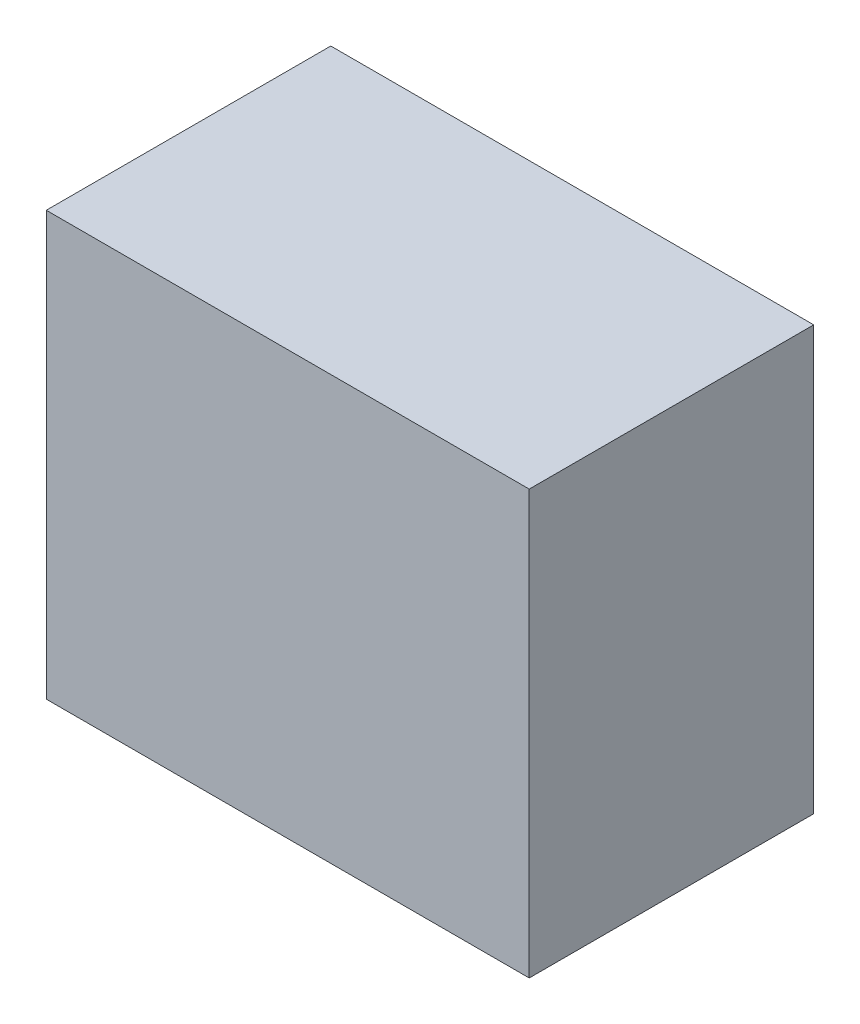
SolidWorks part; units mm, degrees
ref_plane "前视基准面" through (0, 0, 0) normal (0, 0, 1) x (1, 0, 0)
ref_plane "上视基准面" through (0, 0, 0) normal (0, 1, 0) x (1, 0, 0)
ref_plane "右视基准面" through (0, 0, 0) normal (1, 0, 0) x (0, 0, -1)
other "Configuration Table"
sketch "草图2" plane through (0, 0, 0) normal (0, 0, 1) x (1, 0, 0)
  line L1 (-36.5, 32) -> (36.5, 32)
  line L2 (-36.5, 32) -> (-36.5, -32)
  line L3 (-36.5, -32) -> (36.5, -32)
  line L4 (36.5, 32) -> (36.5, -32)
  line L5 (0, -32) -> (0, 32) construction
  line L6 (-36.5, 0) -> (36.5, 0) construction
  point P0 (0, 0)
  dimension "D1" = 73
  dimension "D2" = 64
extrude "凸台-拉伸1" add sketch "草图2" along normal blind 43
